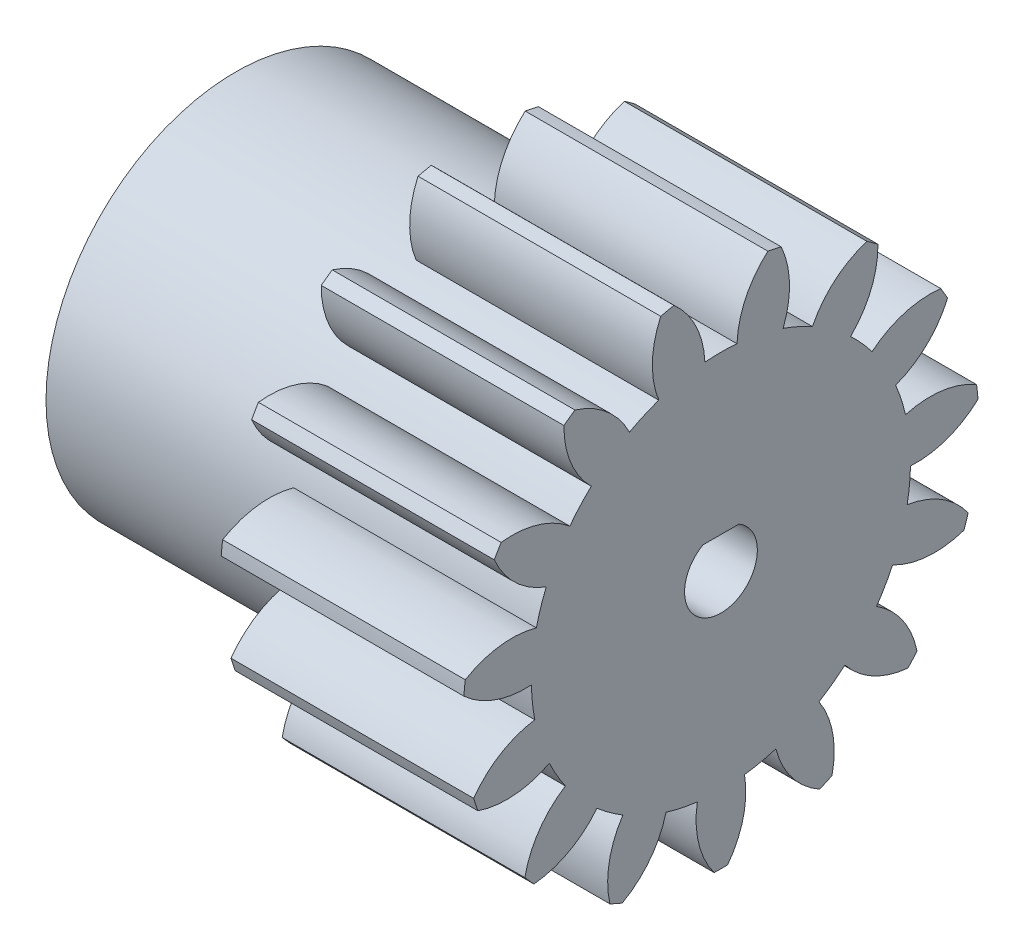
SolidWorks part; units mm, degrees
ref_plane "Plane1" through (0, 0, 0) normal (0, 0, 1) x (1, 0, 0)
ref_plane "Plane2" through (0, 0, 0) normal (0, 1, 0) x (1, 0, 0)
ref_plane "Plane3" through (0, 0, 0) normal (1, 0, 0) x (0, 0, -1)
sketch "HoldingSke" plane through (0, 0, 0) normal (0, 1, 0) x (1, 0, 0)
  line L0 (0, 0) -> (0.7727, -0.2071)
  line L1 (-15, 0) -> (100, 0) construction
  line L2 (0, 0) -> (-2.1039, 2.3779)
  line L3 (0, 0) -> (-11.863, 4.5341)
  line L4 (0, 0) -> (8.3417, 2.2352)
  line L5 (0, 0) -> (-46.8476, -17.4728)
  line L6 (0, 0) -> (-8.2896, -5.593)
  line L7 (-2.1039, 2.3779) -> (8.6586, 51.2059)
  line L8 (-76.2, 54.61) -> (-75.7, 54.61)
  line L9 (-71.009, 38.7566) -> (-53.1078, 45.2721)
  line L10 (-76.2, 71.12) -> (104.1128, 71.12)
  line L11 (0, 0) -> (-10, 0)
  line L12 (-76.2, 101.6) -> (-76.155, 101.6)
  line L13 (24.9733, 27.94) -> (52.9518, 28.4284)
  line L14 (24.9733, 27.94) -> (24.9743, 27.94)
  line L15 (24.9733, 27.94) -> (100.4006, 29.5858)
  line L16 (-63.627, -1.25) -> (-12.827, -1.25)
  circle A0 centre (0, 0) radius 1.5
  circle A1 centre (0, 0) radius 7.8115
  circle A2 centre (0, 0) radius 37.5
  circle A3 centre (0, 0) radius 1.5
  dimension "MHD" = 15.623
  dimension "Hub_dia" = 75
  dimension "Bore" = 3
  dimension "MBD" = 3
  dimension "Num_teeth" = 15
  dimension "Pitch" = 0.8
  dimension "Overall_len" = 50
  dimension "Show_teeth" = 15
  dimension "Thickness" = 10
  dimension "OAL" = 50.0001
  dimension "T_dim" = 0.5
  dimension "Ap" = 20
  dimension "H" = 19.05
  dimension "Pitch_radius" = 180.3128
  dimension "Width" = 10
  dimension "Backlash" = 0.045
  dimension "Addendum_fac" = 1
  dimension "Dedendum_fac" = 1.25
  dimension "Clearance_fac" = 0.25
  dimension "Dedendum_add" = 0.001
  dimension "Module" = 1.25
sketch "BasProSke" plane through (0, 0, 0) normal (0, 1, 0) x (1, 0, 0)
  line L0 (-10, 0) -> (60, 0) construction
  line L1 (0, 0) -> (0, 10.625)
  line L2 (0, 0) -> (10, 0)
  line L3 (10, 0) -> (10, 10.625)
  line L4 (10, 10.625) -> (0, 10.625)
  dimension "Thickness" = 10
  dimension "Diameter" = 21.25
revolve "Base-Revolve" add sketch "BasProSke" angle 360 about L0
sketch "TooCutSke" plane through (0, 0, 0) normal (1, 0, 0) x (0, 0, -1)
  line L1 (0, 0) -> (0, 107) construction
  line L2 (0, 0) -> (-1.0586, 9.315) construction
  line L3 (0, 0) -> (-3.8803, 18.2553) construction
  line L4 (-1.0586, 9.315) -> (-1.9401, 9.1277) construction
  arc A0 (0.6608, 7.7835) -> (-0.6608, 7.7835) centre (0, 0) ccw
  arc A1 (1.9597, 10.4686) -> (-1.9597, 10.4686) centre (0, 0) ccw
  circle A2 centre (0, 0) radius 9.375 construction
  circle A3 centre (0, 0) radius 8.8096 construction
  arc A4 (-0.6608, 7.7835) -> (-1.9597, 10.4686) centre (-4.4076, 7.6277) ccw
  arc A5 (1.9597, 10.4686) -> (0.6608, 7.7835) centre (4.4076, 7.6277) ccw
  dimension "Root_dia" = 15.623
  dimension "Overcut_dia" = 21.3008
  dimension "Pitch_dia" = 18.75
  dimension "Base_dia" = 17.6192
  dimension "Flank_rad" = 3.75
  dimension "Half_ang" = 12
  dimension "Half_CT" = 0.9012
extrude "ToothCut" cut sketch "TooCutSke" along normal through all
fillet "Breaks" [suppressed] radius 0.025
fillet "RootFillets" [suppressed] radius 0.3135
pattern_circular "TeethCuts" count 15 every 24 about axis through (-10, 0, 0) along (1, 0, 0) of "ToothCut", "RootFillets", "Breaks"
sketch "HubNeaOneSke" plane through (0, 0, 0) normal (-1, 0, 0) x (0, 0, 1)
  circle A0 centre (0, 0) radius 7.8115
  dimension "Diameter" = 15.623
extrude "HubNearOne" [suppressed] add sketch "HubNeaOneSke" along normal blind 40.0001
sketch "HubNeaBotSke" plane through (0, 0, 0) normal (-1, 0, 0) x (0, 0, 1)
  circle A0 centre (0, 0) radius 7.8115
  dimension "Diameter" = 15.623
extrude "HubNearBoth" [suppressed] add sketch "HubNeaBotSke" along normal blind 20
ref_plane "FarPln" through (10, 0, 0) normal (1, 0, 0) x (0, 0, -1)
sketch "HubFarSke" plane through (10, 0, 0) normal (1, 0, 0) x (0, 0, -1)
  circle A0 centre (0, 0) radius 7.8115
  dimension "Diameter" = 15.623
extrude "HubFar" [suppressed] add sketch "HubFarSke" along normal blind 20
sketch "BorSke" plane through (0, 0, 0) normal (1, 0, 0) x (0, 0, -1)
  circle A0 centre (0, 0) radius 1.5
  dimension "Diameter" = 3
extrude "Bore" cut sketch "BorSke" along normal mid plane 100.0001
sketch "KeySke" plane through (0, 0, 0) normal (1, 0, 0) x (0, 0, -1)
  line L0 (-0.6, 0) -> (-0.6, 2)
  line L1 (-0.6, 2) -> (0.6, 2)
  line L2 (0.6, 2) -> (0.6, 0)
  line L3 (0, 0) -> (0, 34) construction
  line L4 (-0.6, 0) -> (0.6, 0)
  dimension "Offset" = 2
  dimension "Width" = 1.2
extrude "Keyway" [suppressed] cut sketch "KeySke" along normal mid plane 100.0001
pattern_circular "Keyway2" [suppressed] count 2 every 90 about axis through (-10, 0, 0) along (1, 0, 0)
sketch "Sketch1" plane through (0, 0, 0) normal (-1, 0, 0) x (0, 0, 1)
  circle A0 centre (0, 0) radius 7.8115
  arc A2 (7.6068, 1.7767) -> (7.1983, 3.0337) centre (0, 0) ccw construction
  circle A3 centre (0, 0) radius 1.5 construction
  circle A4 centre (0, 0) radius 1.5
extrude "Boss-Extrude1" add sketch "Sketch1" along normal blind 10
sketch "Sketch2" plane through (10, 0, 0) normal (1, 0, 0) x (0, 0, -1)
  line L0 (-0.7396, 1.305) -> (0.7396, 1.305)
  circle A0 centre (0, 0) radius 1.5 construction
  circle A1 centre (0, 0) radius 1.5
  circle A2 centre (0, 0) radius 1.5 construction
  point P5 (1.1165, 1.0018)
  dimension "D1" = 1.305
extrude "Boss-Extrude2" add sketch "Sketch2" against normal up to surface (20 mm away) contours L0 A1
equation "' \"Module@HoldingSke\" = 6.35"
equation "' \"Num_teeth@HoldingSke\" = 12"
equation "' \"Ap@HoldingSke\" =  20"
equation "' \"Ap@HoldingSke\" = 20"
equation "' \"Width@HoldingSke\" = 0.5 * 25.4"
equation "' \"Hub_dia@HoldingSke\"= 1 * 25.4"
equation "' \"Hub_dia@HoldingSke\" = 1 * 25.4"
equation "' \"Overall_len@HoldingSke\" = 1.0 * 25.4"
equation "' \"Bore@HoldingSke\" = 0.75 * 25.4"
equation "' \"T_dim@HoldingSke\" = 0.1 * 25.4"
equation "' \"Width@KeySke\" = 0.25 * 25.4"
equation "' \"Show_teeth@HoldingSke\" = 13"
equation "' \"Backlash@HoldingSke\" = 0.009 * 25.4"
equation "' \"Addendum_fac@HoldingSke\" = 1.0"
equation "' \"Dedendum_fac@HoldingSke\" = 1.25"
equation "' \"Dedendum_add@HoldingSke\" = 0.00005 * 25.4"
equation "' \"Clearance_fac@HoldingSke\" = 0.25"
equation "\"Pitch@HoldingSke\" = 1 / \"Module@HoldingSke\""
equation "\"Overcut_dia@TooCutSke\" = (\"Num_teeth@HoldingSke\" + 2 * \"Addendum_fac@HoldingSke\") / \"Pitch@HoldingSke\" + 0.002 * 25.4"
equation "\"Pitch_dia@TooCutSke\" = \"Num_teeth@HoldingSke\" / \"Pitch@HoldingSke\""
equation "\"Base_dia@TooCutSke\" = \"Num_teeth@HoldingSke\" / \"Pitch@HoldingSke\" * cos((\"Ap@HoldingSke\"  * 3.14159265 / 180))"
equation "\"Root_dia@TooCutSke\" = (\"Num_teeth@HoldingSke\" + 2) / \"Pitch@HoldingSke\" - 2 * (\"Addendum_fac@HoldingSke\" + \"Dedendum_fac@HoldingSke\") / \"Pitch@HoldingSke\" - \"Dedendum_add@HoldingSke\" * 2"
equation "\"Half_ang@TooCutSke\" = 180 / \"Num_teeth@HoldingSke\""
equation "\"Half_CT@TooCutSke\" = \"Num_teeth@HoldingSke\" / \"Pitch@HoldingSke\" * sin((3.14159265 / 2 / \"Num_teeth@HoldingSke\")) / 2 - 7 * \"Backlash@HoldingSke\" / 4"
equation "\"Flank_rad@TooCutSke\" = \"Num_teeth@HoldingSke\" / \"Pitch@HoldingSke\" / 5"
equation "\"Radius@RootFillets\" = \"Clearance_fac@HoldingSke\" / \"Pitch@HoldingSke\" + \"Dedendum_add@HoldingSke\""
equation "\"Break_rad@Breaks\" = 0.02 / \"Pitch@HoldingSke\""
equation "\"Thickness@HoldingSke\" = \"Width@HoldingSke\""
equation "\"OAL@HoldingSke\" = \"Thickness@HoldingSke\""
equation "\"MHD@HoldingSke\" = (\"Num_teeth@HoldingSke\" + 2) / \"Pitch@HoldingSke\" - 2 * (\"Addendum_fac@HoldingSke\" + \"Dedendum_fac@HoldingSke\")  / \"Pitch@HoldingSke\" - \"Dedendum_add@HoldingSke\" * 2"
equation "\"MBD@HoldingSke\" = (\"Num_teeth@HoldingSke\" + 2) / \"Pitch@HoldingSke\" - 2 * (\"Addendum_fac@HoldingSke\" + \"Dedendum_fac@HoldingSke\")  / \"Pitch@HoldingSke\" - \"Dedendum_add@HoldingSke\" * 2 - 0.002 * 25.4"
equation "\"MHD@HoldingSke\" = ((sgn( \"MHD@HoldingSke\" - \"Hub_dia@HoldingSke\" )-1)*( \"MHD@HoldingSke\" - \"Hub_dia@HoldingSke\" ))/-2+ \"Hub_dia@HoldingSke\""
equation "\"MBD@HoldingSke\" = ((sgn( \"MBD@HoldingSke\" - \"Bore@HoldingSke\" )-1)*( \"MBD@HoldingSke\" - \"Bore@HoldingSke\" ))/-2+ \"Bore@HoldingSke\""
equation "\"OAL@HoldingSke\" = ((sgn( \"OAL@HoldingSke\" - \"Overall_len@HoldingSke\" )+1)*( \"OAL@HoldingSke\" - \"Overall_len@HoldingSke\" ))/2 + \"Overall_len@HoldingSke\" + 0.000002 * 25.4"
equation "\"Num_teeth@TeethCuts\" = int( \"Show_teeth@HoldingSke\" ) + 1"
equation "\"Num_teeth@TeethCuts\" = ((sgn( \"Num_teeth@TeethCuts\" - \"Num_teeth@HoldingSke\" )-1)*( \"Num_teeth@TeethCuts\" - \"Num_teeth@HoldingSke\" ))/-2+ \"Num_teeth@HoldingSke\""
equation "\"Num_teeth@TeethCuts\" = ((sgn( \"Num_teeth@TeethCuts\" - 2.0)+1)*( \"Num_teeth@TeethCuts\" - 2.0))/2 +2.0"
equation "\"Angle@TeethCuts\" = 360.0 / \"Num_teeth@HoldingSke\""
equation "\"Diameter@BasProSke\" = (\"Num_teeth@HoldingSke\" + 2 * \"Addendum_fac@HoldingSke\") / \"Pitch@HoldingSke\""
equation "\"Thickness@BasProSke\"  = \"Thickness@HoldingSke\""
equation "' \"Fillet_rad@BasProSke\" =  \"Thickness@HoldingSke\" * 0.05"
equation "' \"Fillet_rad@BasProSke\" = \"Thickness@HoldingSke\" * 0.05"
equation "\"MHD@HoldingSke\" = ((sgn( \"MHD@HoldingSke\" - \"Root_dia@TooCutSke\" )-1)*( \"MHD@HoldingSke\" - \"Root_dia@TooCutSke\" ))/-2+ \"Root_dia@TooCutSke\""
equation "\"Diameter@HubNeaOneSke\" = \"MHD@HoldingSke\""
equation "\"Length@HubNearOne\" = \"OAL@HoldingSke\" - \"Thickness@BasProSke\""
equation "\"Diameter@HubNeaBotSke\" = \"MHD@HoldingSke\""
equation "\"Length@HubNearBoth\" = ( \"OAL@HoldingSke\" - \"Thickness@BasProSke\" ) / 2.0"
equation "\"Thickness@FarPln\" = \"Thickness@BasProSke\""
equation "\"Diameter@HubFarSke\" = \"MHD@HoldingSke\""
equation "\"Length@HubFar\" = ( \"OAL@HoldingSke\" - \"Thickness@BasProSke\" ) / 2.0"
equation "\"Diameter@BorSke\" = \"MBD@HoldingSke\""
equation "\"D1@Bore\" = \"OAL@HoldingSke\" * 2.0"
equation "\"D1@Keyway\" = \"OAL@HoldingSke\" * 2.0"
equation "\"Offset@KeySke\" = \"T_dim@HoldingSke\" + \"MBD@HoldingSke\" / 2.0"
